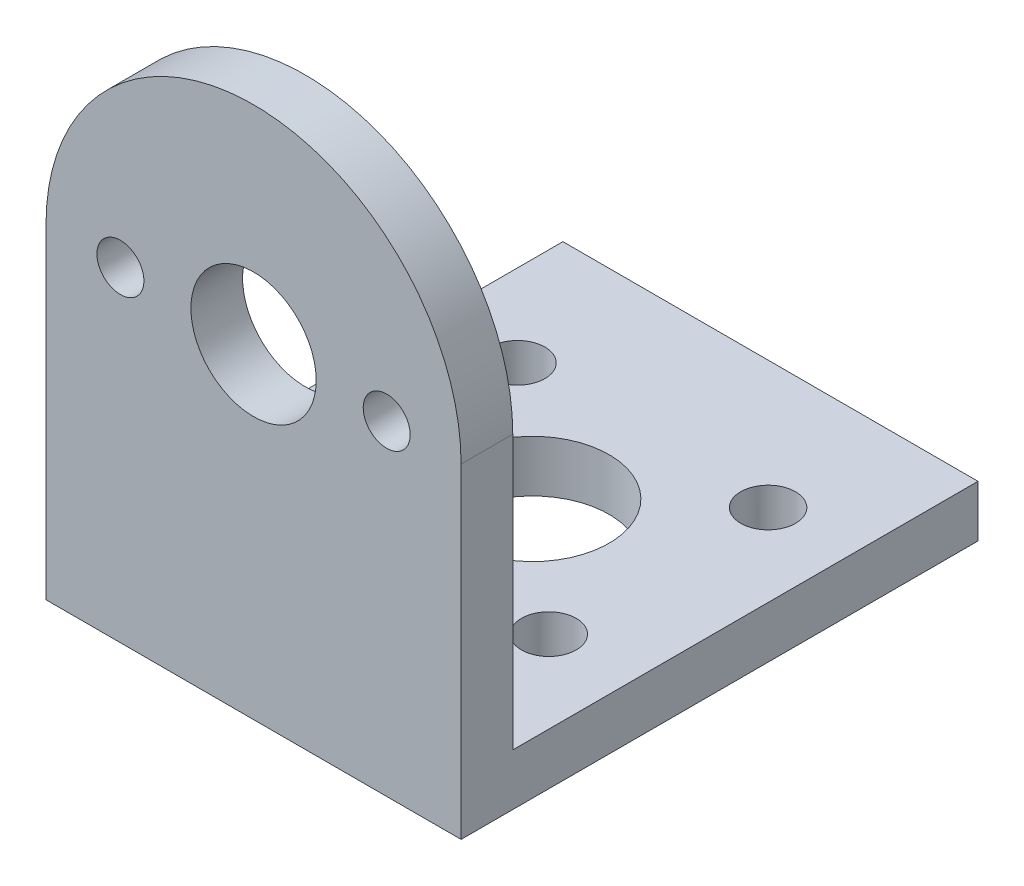
SolidWorks part; units mm, degrees
ref_plane "前视基准面" through (0, 0, 0) normal (0, 0, 1) x (1, 0, 0)
ref_plane "上视基准面" through (0, 0, 0) normal (0, 1, 0) x (1, 0, 0)
ref_plane "右视基准面" through (0, 0, 0) normal (1, 0, 0) x (0, 0, -1)
sketch "草图1" plane through (0, 0, 0) normal (0, 0, 1) x (1, 0, 0)
  line L0 (0, -18.15) -> (0, 18.15) construction
  line L2 (-13.25, 0) -> (-13.25, -20.75)
  line L3 (-13.25, -20.75) -> (13.25, -20.75)
  line L4 (13.25, 0) -> (13.25, -20.75)
  arc A1 (-13.25, 0) -> (13.25, 0) centre (0, 0) cw
  circle A2 centre (0, 0) radius 4
  circle A3 centre (-8.5, 0) radius 1.5
  circle A4 centre (8.5, 0) radius 1.5
  dimension "D1" = 26.5
  dimension "D3" = 8
  dimension "D4" = 3
  dimension "D5" = 8.5
  dimension "D6" = 13.25
  dimension "D2" = 20.75
extrude "凸台-拉伸1" add sketch "草图1" along normal blind 3.3
sketch "草图2" plane through (0, 0, 0) normal (0, 0, 1) x (1, 0, 0)
  line L0 (-13.25, 0) -> (-13.25, -20.75) construction
  line L1 (13.25, -20.75) -> (-13.25, -20.75)
  line L2 (13.25, -20.75) -> (13.25, -17.45)
  line L3 (13.25, -17.45) -> (-13.25, -17.45)
  line L4 (-13.25, -20.75) -> (-13.25, -17.45)
  dimension "D1" = 3.3
extrude "凸台-拉伸2" add sketch "草图2" against normal blind 29.7
sketch "草图3" plane through (0, -17.45, 0) normal (0, 1, 0) x (1, 0, 0)
  line L0 (13.25, 29.7) -> (-13.25, 29.7) construction
  line L1 (-13.25, 29.7) -> (-13.25, 0) construction
  line L2 (0, 14.5) -> (0, 0) construction
  line L3 (0, -18.15) -> (0, 18.15) construction
  circle A0 centre (0, 14.5) radius 4.9
  circle A1 centre (-8, 21.55) radius 1.75
  circle A2 centre (-8, 7.55) radius 1.75
  circle A3 centre (8, 7.55) radius 1.75
  circle A4 centre (8, 21.55) radius 1.75
  dimension "D1" = 9.8
  dimension "D2" = 15.2
  dimension "D3" = 8.15
  dimension "D4" = 3.5
  dimension "D6" = 3.5
  dimension "D7" = 14
  dimension "D8" = 5.25
  dimension "D5" = 5.25
extrude "切除-拉伸1" cut sketch "草图3" against normal up to surface (3.3 mm away) up to face at (0, -20.75, -13.2)
